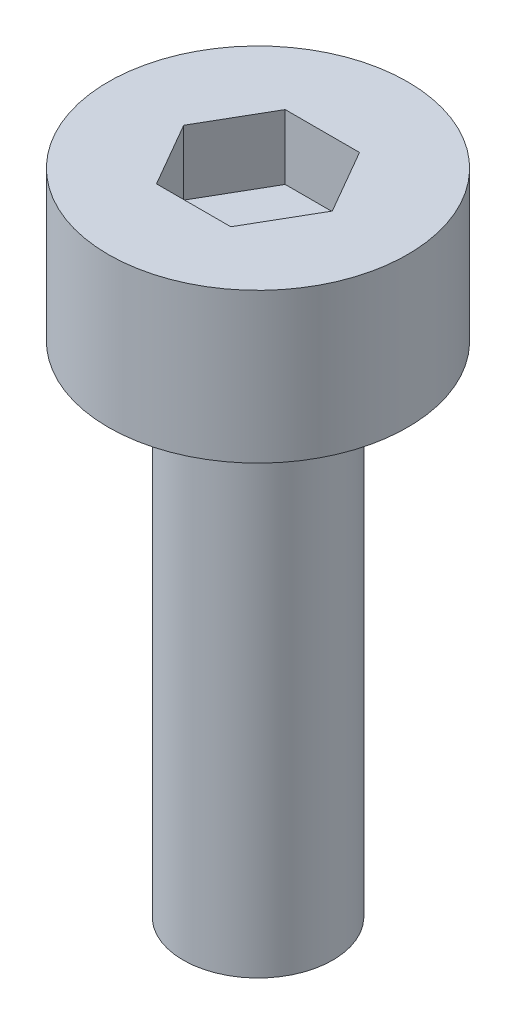
SolidWorks part; units mm, degrees
ref_plane "Front Plane" through (0, 0, 0) normal (0, 0, 1) x (1, 0, 0)
ref_plane "Top Plane" through (0, 0, 0) normal (0, 1, 0) x (1, 0, 0)
ref_plane "Right Plane" through (0, 0, 0) normal (1, 0, 0) x (0, 0, -1)
sketch "Sketch1" plane through (0, 0, 0) normal (0, 1, 0) x (1, 0, 0)
  circle A0 centre (0, 0) radius 1.5
  dimension "D1" = 3
extrude "ScrewShaft" add sketch "Sketch1" along normal blind 10
sketch "Sketch2" plane through (0, 10, 0) normal (0, 1, 0) x (1, 0, 0)
  circle A0 centre (0, 0) radius 3
  dimension "D1" = 6
extrude "Boss-Extrude2" add sketch "Sketch2" along normal blind 3
sketch "Sketch3" plane through (0, 13, 0) normal (0, 1, 0) x (1, 0, 0)
  line L0 (0, 0) -> (0, 1.29) construction
  line L1 (1.4896, 0) -> (0.7448, 1.29)
  line L2 (0.7448, 1.29) -> (-0.7448, 1.29)
  line L3 (-0.7448, 1.29) -> (-1.4896, 0)
  line L4 (-1.4896, 0) -> (-0.7448, -1.29)
  line L5 (-0.7448, -1.29) -> (0.7448, -1.29)
  line L6 (0.7448, -1.29) -> (1.4896, 0)
  circle A0 centre (0, 0) radius 1.29 construction
  dimension "D1" = 2.58
extrude "Cut-Extrude1" cut sketch "Sketch3" against normal blind 1.3
equation "\"X-ROD-SPACING\"=45"
equation "\"Y-ROD-SPACING\"=75"
equation "\"Z-ROD-SPACING\"=17.5"
equation "\"Y-BED-OFFSET\"=2"
equation "\"Y-BED-ROD-INSET\"=3.5"
equation "\"T-SLOT-NUT-FILLET-RADIUS\"=0.5"
equation "\"T-SLOT-SCREW-SHAFT-RADIUS\"=1.55"
equation "\"T-SLOT-SCREW-SHAFT-CUTOUT-LENGTH\"=11"
equation "\"T-SLOT-NUT-DEPTH\"=3.5"
equation "\"T-SLOT-NUT-WIDTH\"=2.85"
equation "\"T-SLOT-NUT-END-DISTANCE\"=8"
equation "\"ACRYLIC-THICKNESS\"=10"
equation "\"ACRYLIC-THICKNESS2\"=4.5"
equation "\"ACRYLIC-TAB-CUTOUT-SIZE\"=\"ACRYLIC-THICKNESS\"+\"ACRYLIC-TAB-TOLERANCE\"*2"
equation "\"ACRYLIC-TAB-WIDTH\"=\"ACRYLIC-THICKNESS\""
equation "\"ACRYLIC-M3-HOLE\"=2.9"
equation "\"SMOOTHROD-CAP-SCREW-DISTANCE\"=20"
equation "\"FRAME-WIDTH-INNER\"=370"
equation "\"NEMA17-HOLE-SPACING\"=31"
equation "\"NEMA17-CENTRAL-CUTOUT\"=22.5"
equation "\"Z-BRACKET-REACH\"=57"
equation "\"TOP-BRACKET-SPACING\"=40"
equation "\"SMOOTHROD-X-LENGTH\"=350"
equation "\"SMOOTHROD-Y-LENGTH\"=350"
equation "\"SMOOTHROD-Z-LENGTH\"=350"
equation "\"SMOOTHROD-TIGHTENING-HEADROOM\"=.25"
equation "\"LEADSCREW-Z-LENGTH\"=300"
equation "\"SCREW-LENGTH-FRAME\"=\"ACRYLIC-THICKNESS\" + 10"
equation "\"SCREW-HEAD-RADIUS\"=6"
equation "\"PRINTED-X-SMOOTHROD-DIAMETER\"=8.8"
equation "\"PRINTED-X-SMOOTHROD-CUTOUT\"=10"
equation "\"PRINTED-X-BASE-HEIGHT\"=10"
equation "\"PRINTED-LM8UU-CUTOUT-SIZE\"=15.5"
equation "\"PRINTED-LM8UU-CUTOUT-LENGTH\"=24.5"
equation "\"PRINTED-X-IDLER-HEIGHT\"=16"
equation "\"PSU-MOUNTING-WIDTH\"=95"
equation "\"PSU-MOUNTING-HEIGHT\"=177"
equation "\"D1@Sketch2\"=\"SCREW-HEAD-RADIUS\""
